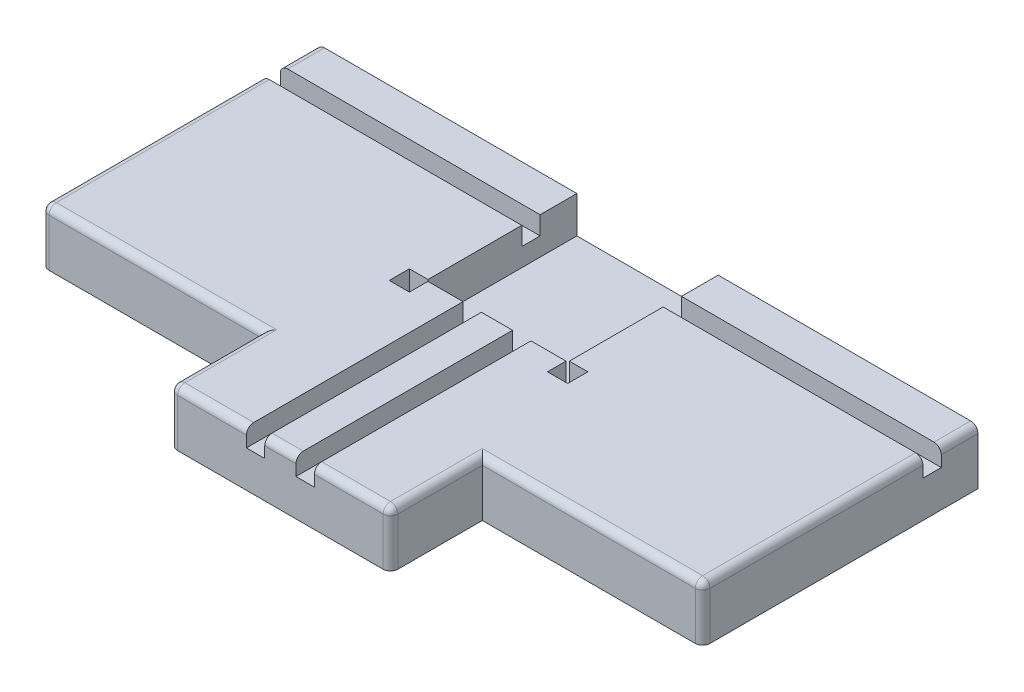
SolidWorks part; units mm, degrees
ref_plane "Front Plane" through (0, 0, 0) normal (0, 0, 1) x (1, 0, 0)
ref_plane "Top Plane" through (0, 0, 0) normal (0, 1, 0) x (1, 0, 0)
ref_plane "Right Plane" through (0, 0, 0) normal (1, 0, 0) x (0, 0, -1)
sketch "Sketch1" plane through (0, 0, 0) normal (0, 1, 0) x (1, 0, 0)
  line L1 (-90, -75) -> (90, -75)
  line L2 (-90, -75) -> (-90, 75)
  line L3 (-90, 75) -> (90, 75)
  line L4 (90, -75) -> (90, 75)
  line L5 (-90, -75) -> (90, 75) construction
  line L6 (-90, 75) -> (90, -75) construction
  point P0 (0, 0)
  dimension "D1" = 180
  dimension "D2" = 150
extrude "Boss-Extrude1" add sketch "Sketch1" along normal blind 15
sketch "Sketch2" plane through (0, 15, 0) normal (0, 1, 0) x (1, 0, 0)
  line L1 (-19.25, -41) -> (19.25, -41)
  line L2 (-19.25, -41) -> (-19.25, 41)
  line L3 (-19.25, 41) -> (19.25, 41)
  line L4 (19.25, -41) -> (19.25, 41)
  line L5 (-19.25, -41) -> (19.25, 41) construction
  line L6 (-19.25, 41) -> (19.25, -41) construction
  point P0 (0, 0)
  dimension "D1" = 82
  dimension "D2" = 38.5
sketch "Sketch7" plane through (0, 0, 0) normal (0, 1, 0) x (1, 0, 0)
  line L0 (0, 75) -> (0, 100) construction
  line L1 (90, 75) -> (-90, 75) construction
  line L2 (-90, -75) -> (90, -75) construction
  line L3 (0, -75) -> (0, -100) construction
  line L5 (-30, 75) -> (30, 75)
  line L6 (-30, 75) -> (-30, 100)
  line L7 (-30, 100) -> (30, 100)
  line L8 (30, 75) -> (30, 100)
  line L9 (-30, 75) -> (30, 100) construction
  line L10 (-30, 100) -> (30, 75) construction
  line L11 (-30, -100) -> (30, -100)
  line L12 (-30, -100) -> (-30, -75)
  line L13 (-30, -75) -> (30, -75)
  line L14 (30, -100) -> (30, -75)
  line L15 (-30, -100) -> (30, -75) construction
  line L16 (-30, -75) -> (30, -100) construction
  point P7 (0, 87.5)
  point P15 (0, -87.5)
  dimension "D1" = 25
  dimension "D2" = 25
  dimension "D3" = 60
  dimension "D4" = 60
extrude "Boss-Extrude6" add sketch "Sketch7" along normal blind 15 contours L11 L14 L13 L12 | L5 L8 L7 L6
fillet "Fillet1" radius 2 20 edges at (90, 7.5, -75) (90, 7.5, 75) (30, 7.5, -100) (30, 15, -87.5) (60, 15, -75) (0, 15, -100) (-30, 15, -87.5) (-60, 15, -75) (-60, 15, 75) (-30, 15, 87.5) (30, 15, 87.5) (60, 15, 75) (90, 15, 0) (-90, 15, 0) (0, 15, 100) (30, 7.5, 100) (-30, 7.5, 100) (-90, 7.5, 75) (-90, 7.5, -75) (-30, 7.5, -100)
sketch "Sketch10" plane through (0, 15, 0) normal (0, 1, 0) x (1, 0, 0)
  line L0 (-9.25, -40.5) -> (-9.25, -33.1629)
  line L15 (-99.0229, 15) -> (-19.25, 15)
  line L22 (-99.0229, 10) -> (-19.25, 10)
  line L24 (-9.25, -105.688) -> (-4.25, -105.688)
  line L27 (-4.25, -105.688) -> (-4.25, -40.5)
  line L32 (-99.0229, 15) -> (-99.0229, 10)
  line L33 (-9.25, -40.5) -> (-9.25, -105.688)
  line L34 (-9.25, -33.1629) -> (-4.25, -33.1629)
  line L35 (-4.25, -33.1629) -> (-4.25, -40.5)
  line L36 (-19.25, 10) -> (-11.5551, 10)
  line L37 (-11.5551, 10) -> (-11.5551, 15)
  line L38 (-11.5551, 15) -> (-19.25, 15)
  dimension "D3" = 5
  dimension "D6" = 5
extrude "Cut-Extrude1" cut sketch "Sketch2" along direction (0, -1, 0) on the side against the normal blind 10
extrude "Cut-Extrude3" cut sketch "Sketch10" against normal blind 5
sketch "Sketch11" plane through (0, 15, 0) normal (0, 1, 0) x (1, 0, 0)
  line L6 (-19.25, 41) -> (-24.2997, 46.0497) construction
  line L8 (-24.2997, 46.0497) -> (-18.7997, 46.0497)
  line L9 (-24.2997, 46.0497) -> (-24.2997, 40.5497)
  line L10 (-24.2997, 40.5497) -> (-18.7997, 40.5497)
  line L11 (-18.7997, 46.0497) -> (-18.7997, 40.5497)
  dimension "D1" = 7.1414
  dimension "D2" = 5.5
  dimension "D3" = 5.5
extrude "Cut-Extrude6" cut sketch "Sketch11" against normal blind 7
mirror "Mirror3" about plane through (0, 0, 0) normal (1, 0, 0) of "Cut-Extrude6" second plane through (0, 0, 0) second plane normal (0, 0, 1)
mirror "Mirror4" about plane through (0, 0, 0) normal (1, 0, 0) of "Cut-Extrude3" second plane through (0, 0, 0) second plane normal (0, 0, 1)
sketch "Sketch12" plane through (0, 0, 0) normal (0, 0, 1) x (1, 0, 0)
  line L1 (-95.5421, 18.3786) -> (99.1367, 18.3786)
  line L2 (-95.5421, 18.3786) -> (-95.5421, -5.0813)
  line L3 (-95.5421, -5.0813) -> (99.1367, -5.0813)
  line L4 (99.1367, 18.3786) -> (99.1367, -5.0813)
extrude "Cut-Extrude7" cut sketch "Sketch12" against normal through all
